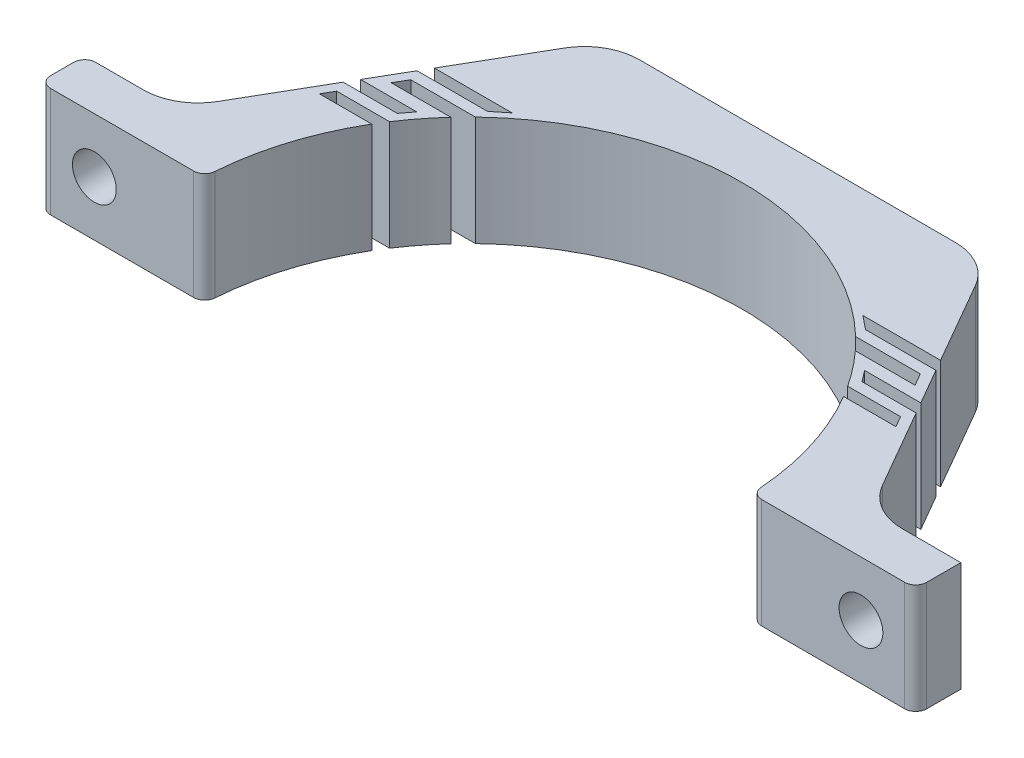
SolidWorks part; units mm, degrees
ref_plane "前视基准面" through (0, 0, 0) normal (0, 0, 1) x (1, 0, 0)
ref_plane "上视基准面" through (0, 0, 0) normal (0, 1, 0) x (1, 0, 0)
ref_plane "右视基准面" through (0, 0, 0) normal (1, 0, 0) x (0, 0, -1)
sketch "草图1" plane through (0, 0, 0) normal (0, 1, 0) x (1, 0, 0)
  line L0 (-17.2481, 19) -> (-23.6672, 19)
  line L1 (14.4571, 29.9888) -> (-14.4105, 30.0112)
  line L2 (-18.7425, 27.5146) -> (-23.0888, 20)
  line L7 (-16, 20) -> (-23.0888, 20)
  line L8 (-23.0888, 20) -> (-16, 20)
  line L9 (-39, 0.885) -> (-25.9316, 0.885)
  line L10 (-17.3494, 18) -> (-23.2456, 18)
  line L11 (-26.1386, 14.7271) -> (-30.3206, 7.4966)
  line L12 (-17.2481, 19) -> (-16, 20)
  line L13 (-26.3002, 12.7189) -> (-21.5228, 12.7189)
  line L14 (23.6698, 19) -> (25.5555, 15.7353)
  line L15 (-20.8996, 13.7189) -> (-25.7218, 13.7189)
  line L16 (-20.4268, 15.7353) -> (-25.5555, 15.7353)
  line L17 (-18.4522, 16.8677) -> (-23.9005, 16.8677)
  line L18 (-21.2018, 14.7271) -> (-26.1386, 14.7271)
  line L19 (21.2018, 14.7271) -> (20.4268, 15.7353)
  line L20 (-25.7218, 13.7189) -> (-26.3002, 12.7189)
  line L21 (-23.9005, 16.8677) -> (-23.2456, 18)
  line L22 (23.9005, 16.8677) -> (23.2456, 18)
  line L23 (25.7218, 13.7189) -> (26.3002, 12.7189)
  line L24 (-21.2018, 14.7271) -> (-20.4268, 15.7353)
  line L25 (-23.6672, 19) -> (-25.5555, 15.7353)
  line L26 (21.2018, 14.7271) -> (26.1386, 14.7271)
  line L27 (18.4522, 16.8677) -> (23.9005, 16.8677)
  line L28 (20.4268, 15.7353) -> (25.5555, 15.7353)
  line L29 (20.8996, 13.7189) -> (25.7218, 13.7189)
  line L30 (26.3002, 12.7189) -> (21.5228, 12.7189)
  line L31 (17.2507, 19) -> (16.0026, 20)
  line L32 (17.3494, 18) -> (23.2456, 18)
  line L33 (23.0914, 20) -> (16.0026, 20)
  line L34 (16.0026, 20) -> (23.0914, 20)
  line L35 (17.2507, 19) -> (23.6698, 19)
  line L36 (18.7872, 27.482) -> (23.0914, 20)
  line L37 (-34.6488, 5) -> (-39, 5)
  line L38 (-40, 4) -> (-40, 1.885)
  line L41 (40.0077, 4.9379) -> (40.0029, 1.8229)
  line L42 (34.6565, 4.9462) -> (40.0077, 4.9379)
  line L43 (39.0013, 0.8245) -> (25.9329, 0.8448)
  line L44 (30.3322, 7.4495) -> (26.1381, 14.7271)
  arc A0 (18.4522, 16.8677) -> (20.8996, 13.7189) centre (0, 0) cw
  arc A1 (-18.4522, 16.8677) -> (-20.8996, 13.7189) centre (0, 0) ccw
  arc A2 (-21.5228, 12.7189) -> (-24.9342, 1.8125) centre (0, 0) ccw
  arc A3 (17.3494, 18) -> (-17.3494, 18) centre (0, 0) ccw
  arc A4 (20.8996, 13.7189) -> (18.4522, 16.8677) centre (0, 0) ccw
  arc A5 (24.937, 1.7738) -> (21.5228, 12.7189) centre (0, 0) ccw
  arc A6 (39.0013, 0.8245) -> (40.0029, 1.8229) centre (39.0029, 1.8245) ccw
  arc A7 (-34.6488, 5) -> (-30.3206, 7.4966) centre (-34.6488, 10) ccw
  arc A8 (34.6565, 4.9462) -> (30.3322, 7.4495) centre (34.6643, 9.9462) cw
  arc A9 (-14.4105, 30.0112) -> (-18.7425, 27.5146) centre (-14.4143, 25.0112) ccw
  arc A10 (18.7872, 27.482) -> (14.4571, 29.9888) centre (14.4532, 24.9888) ccw
  arc A11 (25.9329, 0.8448) -> (24.937, 1.7738) centre (25.9345, 1.8448) cw
  arc A12 (-40, 4) -> (-39, 5) centre (-39, 4) cw
  arc A13 (-39, 0.885) -> (-40, 1.885) centre (-39, 1.885) cw
  arc A14 (-25.9316, 0.885) -> (-24.9342, 1.8125) centre (-25.9316, 1.885) ccw
  dimension "D1" = 1
extrude "凸台-拉伸1" add sketch "草图1" along normal blind 10 contours L9 A14 A2 L13 L20 L15 A1 L17 L21 L10 A3 L32 L22 L27 A0 L29 L23 L30 A5 A11 L43 A6 L41 L42 A8 L44 L26 L19 L28 L14 L35 L31 L33 L36 A10 L1 A9 L2 L7 L12 L0 L25 L16 L24 L18 L11 A7 L37 A12 L38 A13
sketch "草图2" plane through (0, 0, 0) normal (0, 0, 1) x (1, 0, 0)
  line L0 (0, 0) -> (0, 5)
  line L1 (0, 5) -> (-35, 5)
  line L2 (0, 5) -> (35, 5)
  circle A0 centre (35, 5) radius 2
  circle A1 centre (-35, 5) radius 2
extrude "切除-拉伸1" cut sketch "草图2" against normal blind 10
